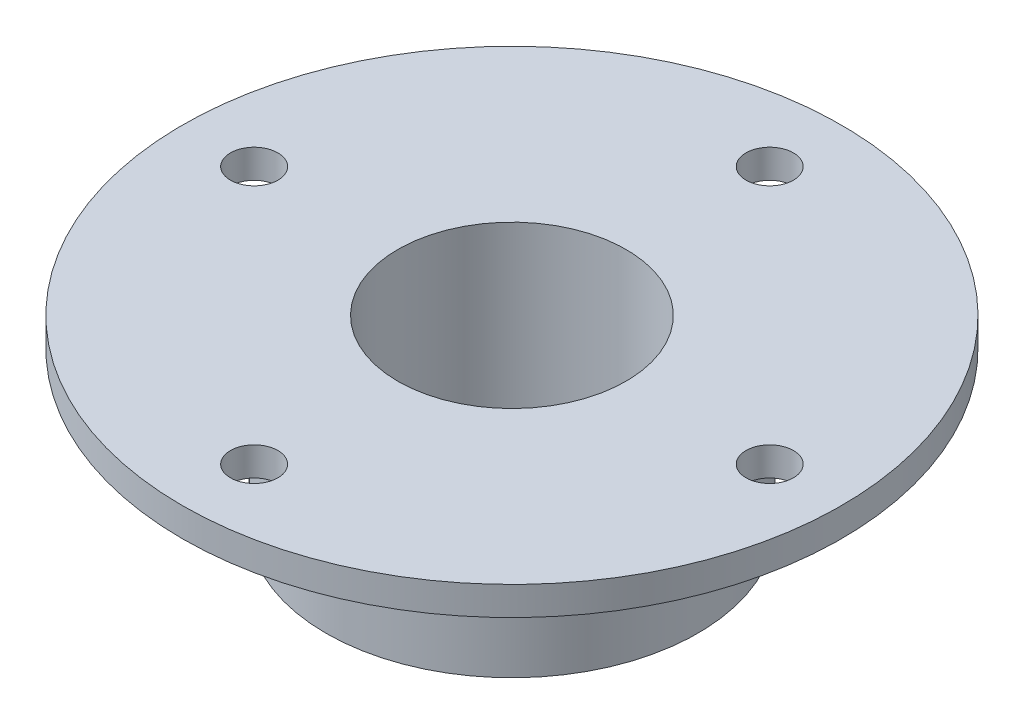
SolidWorks part; units mm, degrees
ref_plane "Front Plane" through (0, 0, 0) normal (0, 0, 1) x (1, 0, 0)
ref_plane "Top Plane" through (0, 0, 0) normal (0, 1, 0) x (1, 0, 0)
ref_plane "Right Plane" through (0, 0, 0) normal (1, 0, 0) x (0, 0, -1)
sketch "Sketch1" plane through (0, 0, 0) normal (0, 0, 1) x (1, 0, 0)
  line L0 (0, 15.5424) -> (0, -16.1471) construction
  line L1 (-7.95, 12.3976) -> (-22.95, 12.3976)
  line L2 (-22.95, 12.3976) -> (-22.95, 10.3976)
  line L3 (-22.95, 10.3976) -> (-12.95, 10.3976)
  line L4 (-12.95, 10.3976) -> (-12.95, -0.3024)
  line L5 (-12.95, -0.3024) -> (-7.95, -0.3024)
  line L6 (-7.95, -0.3024) -> (-7.95, 12.3976)
  point P9 (-10.45, -0.3024)
  dimension "D1" = 12.7
  dimension "D2" = 2
  dimension "D3" = 7.95
  dimension "D4" = 5
  dimension "D5" = 15
revolve "Revolve1" add sketch "Sketch1" angle 360 about L0
sketch "Sketch2" plane through (0, 0, 0) normal (1, 0, 0) x (0, 0, -1)
  line L4 (22.95, 10.3976) -> (-26.666, 10.3976) construction
  line L5 (12.95, -0.3024) -> (-19.4633, -0.3024) construction
  circle A0 centre (0, 5.0476) radius 1.65
  point P0 (0, 5.0476)
  dimension "D3" = 3.3
  dimension "D1" = 10.7
  dimension "D2" = 5.35
hole_wizard "M3.5 Clearance Hole1" positions "Sketch2" profile "Sketch5" hole size "M3.5" standard "AS"
sketch "Sketch5" plane through (0, 5.0476, 0) normal (0, 1, 0) x (0, 0, 1)
  line L0 (0, 0) -> (0, 15.1417)
  line L1 (0, 15.1417) -> (1.95, 13.97)
  line L2 (1.95, 13.97) -> (1.95, 0)
  line L5 (1.95, 0) -> (0, 0)
  line L10 (0, 15.1417) -> (-1.95, 13.97) construction
  line L11 (0, -6.35) -> (0, 107.95) construction
  dimension "Hole Dia." = 3.9
  dimension "Hole Depth" = 13.97
  dimension "Drill Angle" = 118
sketch "Sketch6" plane through (0, 10.3976, 0) normal (0, -1, 0) x (1, 0, 0)
  line L0 (0, 24.4339) -> (0, -26.3529) construction
  circle A0 centre (0, 17.95) radius 1.65
  circle A1 centre (17.95, 0) radius 1.65
  circle A2 centre (0, -17.95) radius 1.65
  circle A3 centre (-17.95, 0) radius 1.65
  point P14 (0, 0)
  dimension "D1" = 3.3
  dimension "D2" = 17.95
  dimension "D3" = 4
extrude "Cut-Extrude1" cut sketch "Sketch6" against normal up to surface (2 mm away) contours A0 L0 | L0 A0 | A1 | L0 A2 | A2 L0 | A3 up to face at (0, 12.3976, 22.95)
